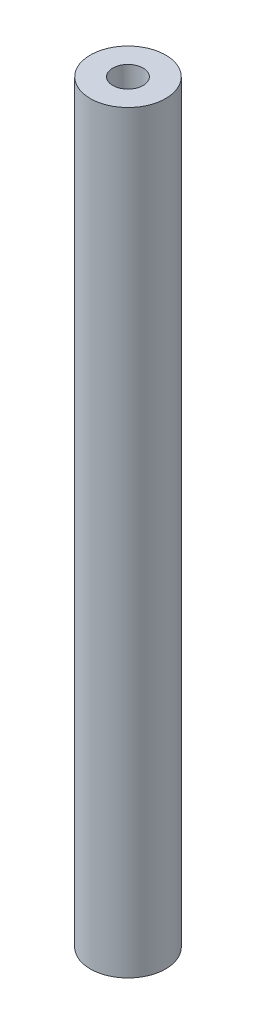
SolidWorks part; units mm, degrees
ref_plane "Front Plane" through (0, 0, 0) normal (0, 0, 1) x (1, 0, 0)
ref_plane "Top Plane" through (0, 0, 0) normal (0, 1, 0) x (1, 0, 0)
ref_plane "Right Plane" through (0, 0, 0) normal (1, 0, 0) x (0, 0, -1)
sketch "Sketch1" plane through (0, 0, 0) normal (0, 1, 0) x (1, 0, 0)
  line L0 (-6.35, 6.35) -> (6.35, 6.35)
  line L1 (-6.35, 6.35) -> (-6.35, -6.35)
  line L2 (6.35, 6.35) -> (6.35, -6.35)
  line L3 (-6.35, -6.35) -> (6.35, -6.35)
  line L4 (-6.35, 6.35) -> (6.35, -6.35) construction
  line L5 (6.35, 6.35) -> (-6.35, -6.35) construction
  circle A0 centre (0, 0) radius 6.35
extrude "Boss-Extrude1" add sketch "Sketch1" along normal blind 127 contours A0
hole_wizard "1/4-20 Tapped Hole3" positions "Sketch8" profile "Sketch7" tap size "1/4-20" standard "ANSI Inch"
sketch "Sketch8" plane through (0, 127, 0) normal (0, 1, 0) x (1, 0, 0)
  point P0 (0, 0)
sketch "Sketch7" plane through (0, 127, 0) normal (1, 0, 0) x (0, 0, 1)
  line L0 (0, 0) -> (0, 18.0438)
  line L1 (0, 18.0438) -> (2.5527, 16.51)
  line L2 (2.5527, 16.51) -> (2.5527, 0)
  line L5 (2.5527, 0) -> (0, 0)
  line L10 (0, 18.0438) -> (-2.5527, 16.51) construction
  line L11 (0, -6.35) -> (0, 107.95) construction
  dimension "Tap Drill Dia." = 5.1054
  dimension "Tap Drill Depth" = 16.51
  dimension "Drill Angle" = 118
hole_wizard "1/4-20 Tapped Hole4" positions "Sketch10" profile "Sketch9" tap size "1/4-20" standard "ANSI Inch"
sketch "Sketch10" plane through (0, 0, 0) normal (0, -1, 0) x (-1, 0, 0)
  point P0 (0, 0)
sketch "Sketch9" plane through (0, 0, 0) normal (1, 0, 0) x (0, 0, -1)
  line L0 (0, 0) -> (0, 18.0438)
  line L1 (0, 18.0438) -> (2.5527, 16.51)
  line L2 (2.5527, 16.51) -> (2.5527, 0)
  line L5 (2.5527, 0) -> (0, 0)
  line L10 (0, 18.0438) -> (-2.5527, 16.51) construction
  line L11 (0, -6.35) -> (0, 107.95) construction
  dimension "Tap Drill Dia." = 5.1054
  dimension "Tap Drill Depth" = 16.51
  dimension "Drill Angle" = 118
